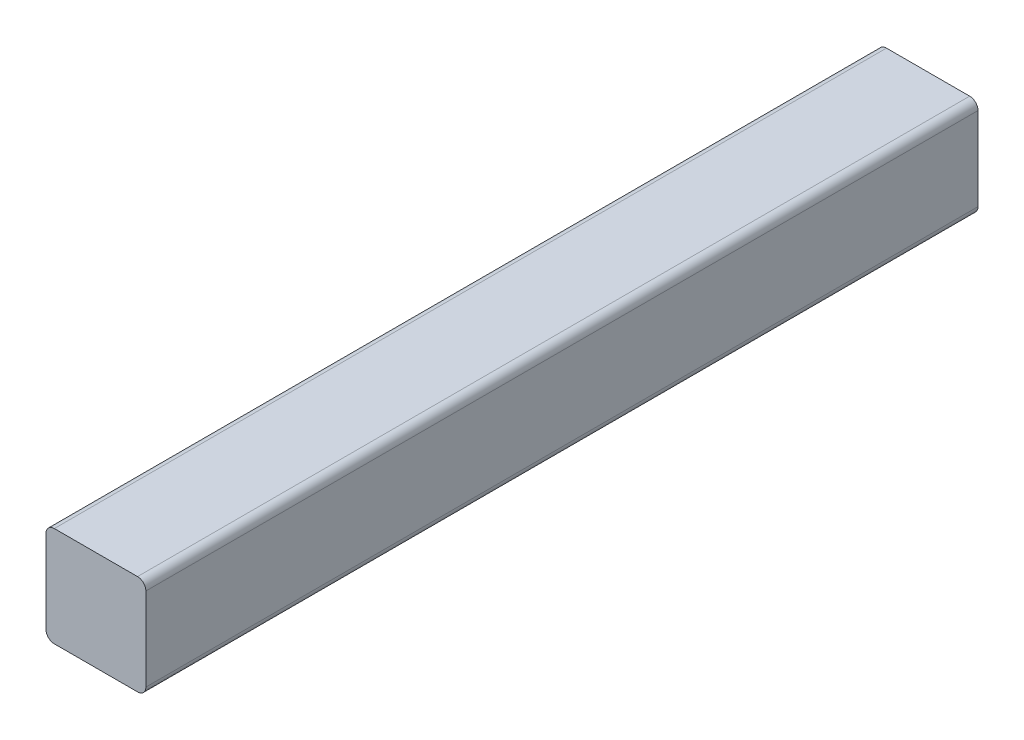
SolidWorks part; units mm, degrees
ref_plane "Front Plane" through (0, 0, 0) normal (0, 0, 1) x (1, 0, 0)
ref_plane "Top Plane" through (0, 0, 0) normal (0, 1, 0) x (1, 0, 0)
ref_plane "Right Plane" through (0, 0, 0) normal (1, 0, 0) x (0, 0, -1)
sketch "Sketch1" plane through (0, 0, 0) normal (0, 0, 1) x (1, 0, 0)
  line L1 (-19.05, -19.05) -> (19.05, -19.05)
  line L2 (-19.05, -19.05) -> (-19.05, 19.05)
  line L3 (-19.05, 19.05) -> (19.05, 19.05)
  line L4 (19.05, -19.05) -> (19.05, 19.05)
  line L5 (-19.05, -19.05) -> (19.05, 19.05) construction
  line L6 (-19.05, 19.05) -> (19.05, -19.05) construction
  point P0 (0, 0)
  dimension "D1" = 38.1
  dimension "D2" = 38.1
extrude "Boss-Extrude1" add sketch "Sketch1" along normal blind 317.5
fillet "Fillet1" radius 3.175 4 edges at (-19.05, 19.05, 158.75) (-19.05, -19.05, 158.75) (19.05, -19.05, 158.75) (19.05, 19.05, 158.75)
